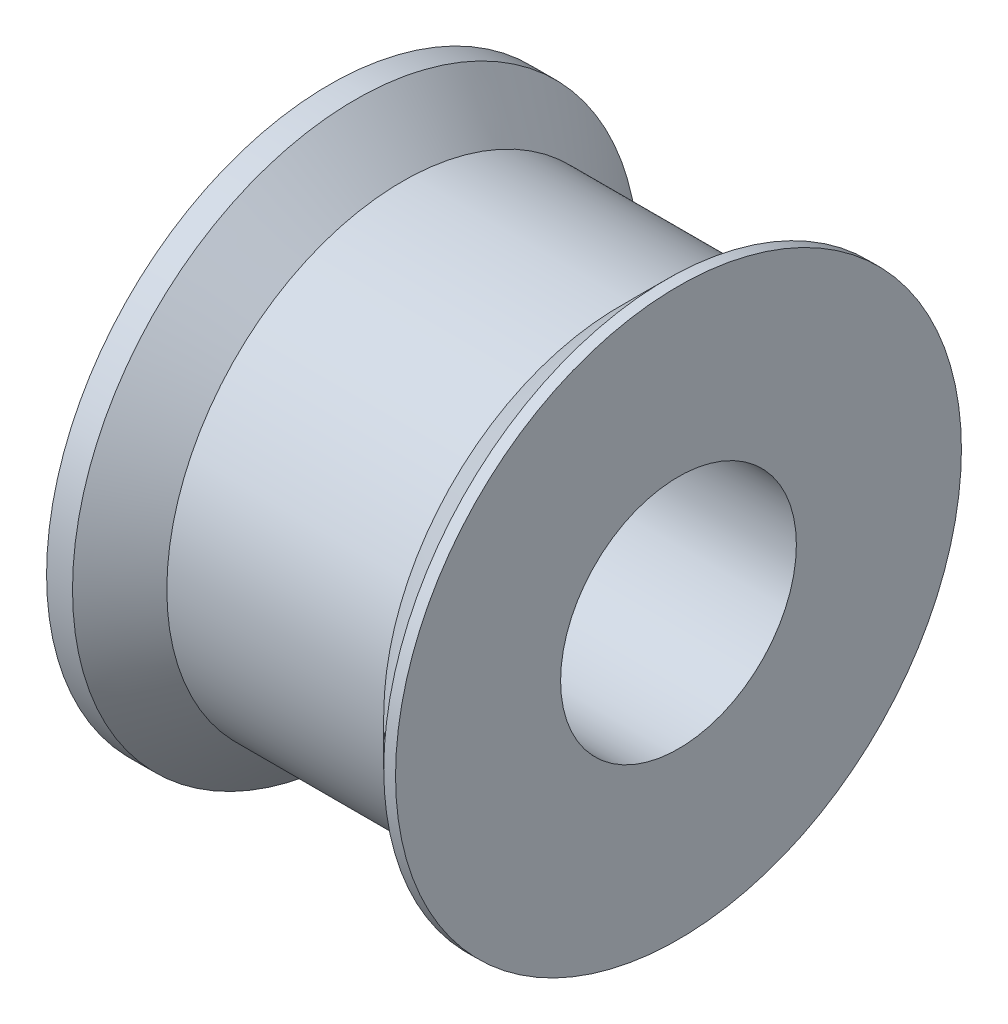
SolidWorks part; units mm, degrees
ref_plane "Front Plane" through (0, 0, 0) normal (0, 0, 1) x (1, 0, 0)
ref_plane "Top Plane" through (0, 0, 0) normal (0, 1, 0) x (1, 0, 0)
ref_plane "Right Plane" through (0, 0, 0) normal (1, 0, 0) x (0, 0, -1)
sketch "Sketch2" plane through (0, 0, 0) normal (0, 1, 0) x (1, 0, 0)
  line L0 (-7.1, 12) -> (-6.6, 12)
  line L1 (-6.6, 12) -> (-4.6, 10)
  line L2 (-4.6, 10) -> (4.6, 10)
  line L3 (4.6, 10) -> (6.6, 12)
  line L4 (6.6, 12) -> (7.1, 12)
  line L5 (7.1, 12) -> (7.1, 0)
  line L6 (-7.1, 12) -> (-7.1, 0) construction
  line L7 (-54.6936, 0) -> (47.2254, 0) construction
  line L8 (0, -23.2469) -> (0, 34.557) construction
  line L9 (7.1, 0) -> (-7.1, 0)
  line L10 (-7.1, 12) -> (-7.7, 12)
  line L11 (-7.7, 12) -> (-7.7, 0)
  line L12 (-7.7, 0) -> (-7.1, 0)
  line L13 (-7.1, 0) -> (-7.7, 0)
  point P16 (0, 10)
  dimension "D1" = 12
  dimension "D2" = 2.5
  dimension "D3" = 9.2
  dimension "D4" = 10
  dimension "D5" = 0.6
revolve "Revolve1" add sketch "Sketch2" angle 360 about L9
sketch "Sketch3" plane through (-7.7, 0, 0) normal (-1, 0, 0) x (0, 0, 1)
  circle A0 centre (0, 0) radius 3.1
  dimension "D1" = 6.2
extrude "Cut-Extrude1" cut sketch "Sketch3" against normal up to surface (14.8 mm away) up to face at (7.1, 0, -12)
sketch "Sketch4" plane through (-7.7, 0, 0) normal (-1, 0, 0) x (0, 0, 1)
  circle A0 centre (0, 0) radius 5
  dimension "D1" = 10
extrude "Cut-Extrude2" cut sketch "Sketch4" against normal up to surface (12.8 mm away) from offset 2 up to face at (7.1, 0, 3.1) offset against normal yes
